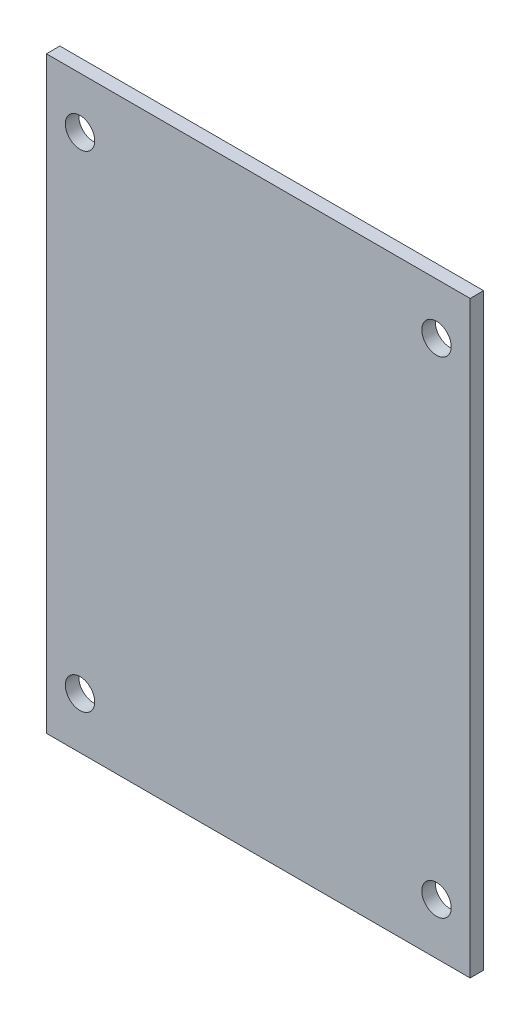
SolidWorks part; units mm, degrees
ref_plane "Plan de face" through (0, 0, 0) normal (0, 0, 1) x (1, 0, 0)
ref_plane "Plan de dessus" through (0, 0, 0) normal (0, 1, 0) x (1, 0, 0)
ref_plane "Plan de droite" through (0, 0, 0) normal (1, 0, 0) x (0, 0, -1)
sketch "Esquisse1" plane through (0, 0, 0) normal (0, 0, 1) x (1, 0, 0)
  line L1 (0, 0) -> (50.4, 0)
  line L2 (0, 0) -> (0, 70)
  line L3 (0, 70) -> (50.4, 70)
  line L4 (50.4, 0) -> (50.4, 70)
  dimension "D1" = 70
  dimension "D2" = 50.4
extrude "Boss.-Extru.1" add sketch "Esquisse1" along normal blind 1.6
sketch "Esquisse2" plane through (0, 0, 1.6) normal (0, 0, 1) x (1, 0, 0)
  line L0 (50.4, 70) -> (0, 70) construction
  line L1 (0, 70) -> (0, 0) construction
  circle A0 centre (4, 63.9) radius 1.75
  point P4 (25.2, 70)
  point P7 (0, 35)
  dimension "D1" = 3.5
  dimension "D2" = 21.2
  dimension "D3" = 28.9
extrude "Enlèv. mat.-Extru.1" cut sketch "Esquisse2" against normal through all
ref_plane "Plan1" through (25.2, 0, 0) normal (-1, 0, 0) x (0, 0, 1)
ref_plane "Plan2" through (0, 35, 0) normal (0, 1, 0) x (1, 0, 0)
mirror "Symétrie1" about plane through (25.2, 0, 0) normal (-1, 0, 0) of "Enlèv. mat.-Extru.1"
mirror "Symétrie2" about plane through (0, 35, 0) normal (0, 1, 0) of "Symétrie1", "Enlèv. mat.-Extru.1"
